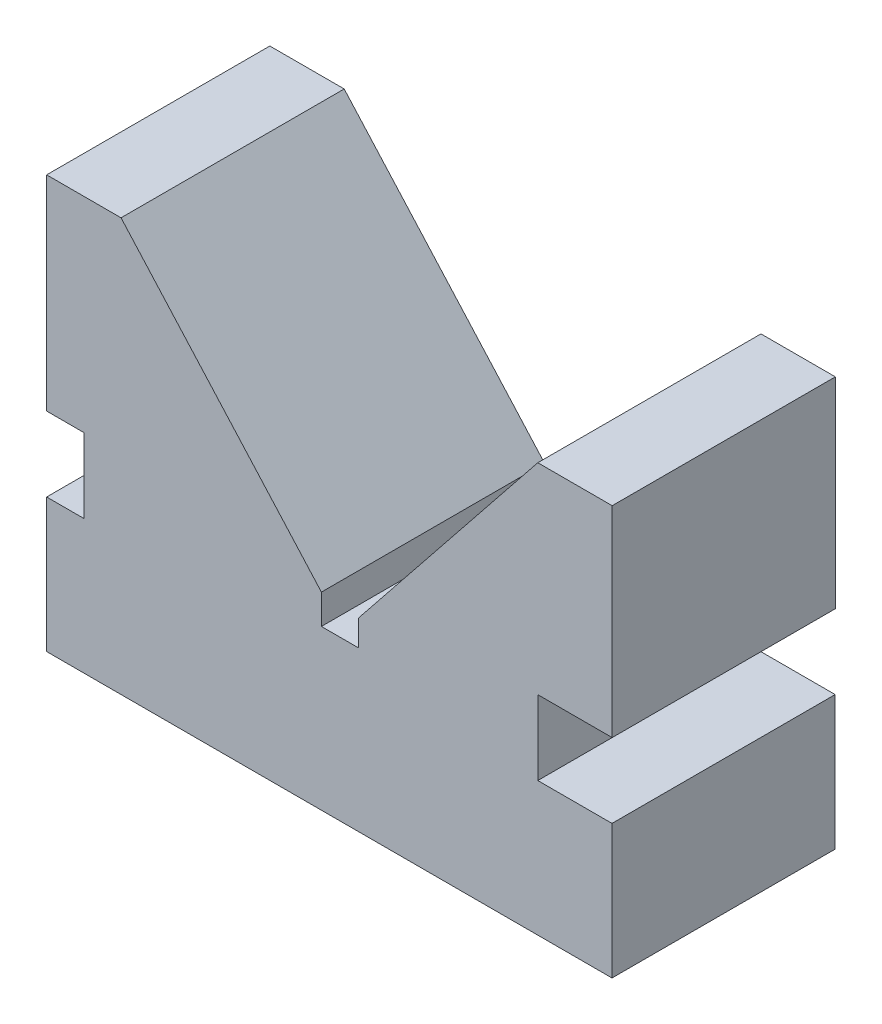
SolidWorks part; units mm, degrees
ref_plane "Front Plane" through (0, 0, 0) normal (0, 0, 1) x (1, 0, 0)
ref_plane "Top Plane" through (0, 0, 0) normal (0, 1, 0) x (1, 0, 0)
ref_plane "Right Plane" through (0, 0, 0) normal (1, 0, 0) x (0, 0, -1)
sketch "Sketch1" plane through (0, 0, 0) normal (0, 0, 1) x (1, 0, 0)
  line L0 (0, 0) -> (76, 0)
  line L1 (76, 0) -> (76, 18)
  line L2 (76, 18) -> (66.0239, 18)
  line L3 (66.0239, 18) -> (66.0239, 28)
  line L4 (66.0239, 28) -> (76.0239, 28)
  line L5 (76.0239, 28) -> (76.0239, 55)
  line L6 (76.0239, 55) -> (66.0239, 55)
  line L7 (66.0239, 55) -> (41.9356, 24.8902)
  line L8 (41.9356, 24.8902) -> (41.9356, 21.3938)
  line L9 (41.9356, 21.3938) -> (36.9356, 21.3938)
  line L10 (36.9356, 21.3938) -> (36.9356, 25.3938)
  line L11 (36.9356, 25.3938) -> (10, 55.5036)
  line L12 (10, 55.5036) -> (0, 55.5036)
  line L13 (0, 55.5036) -> (0, 28)
  line L14 (0, 28) -> (5, 28)
  line L15 (5, 28) -> (5, 18)
  line L16 (5, 18) -> (0, 18)
  line L17 (0, 18) -> (0, 0)
  dimension "D1" = 76
  dimension "D2" = 18
  dimension "D3" = 10
  dimension "D4" = 27
  dimension "D5" = 10
  dimension "D6" = 10
  dimension "D7" = 10
  dimension "D8" = 18
  dimension "D9" = 4
  dimension "D10" = 5
  dimension "D11" = 5
extrude "Boss-Extrude1" add sketch "Sketch1" along normal blind 30 contours L17 L0 L1 L2 L3 L4 L5 L6 L7 L8 L9 L10 L11 L12 L13 L14 L15 L16
